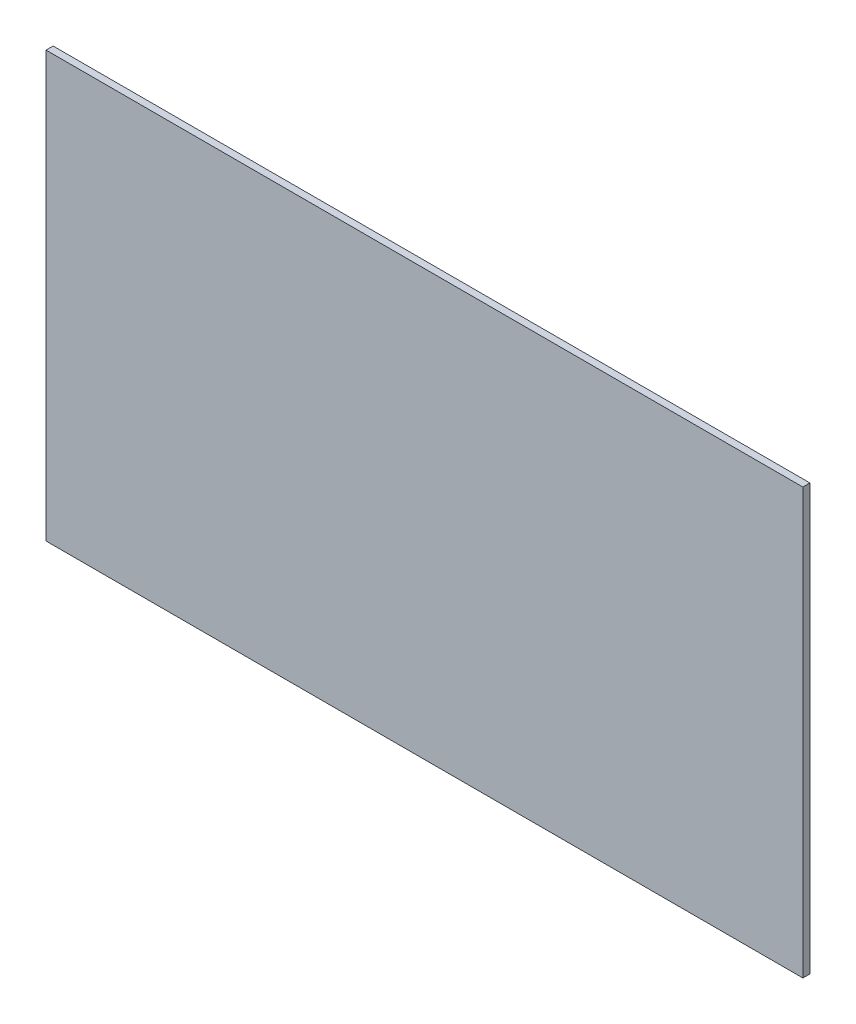
SolidWorks part; units mm, degrees
ref_plane "前基準面" through (0, 0, 0) normal (0, 0, 1) x (1, 0, 0)
ref_plane "上基準面" through (0, 0, 0) normal (0, 1, 0) x (1, 0, 0)
ref_plane "右基準面" through (0, 0, 0) normal (1, 0, 0) x (0, 0, -1)
sketch "草圖1" plane through (0, 0, 0) normal (0, 0, 1) x (1, 0, 0)
  line L1 (-267, 150) -> (267, 150)
  line L2 (-267, 150) -> (-267, -150)
  line L3 (-267, -150) -> (267, -150)
  line L4 (267, 150) -> (267, -150)
  line L5 (-267, 150) -> (267, -150) construction
  line L6 (-267, -150) -> (267, 150) construction
  point P0 (0, 0)
  dimension "D1" = 300
  dimension "D2" = 534
extrude "填料-伸長1" add sketch "草圖1" along normal blind 5
